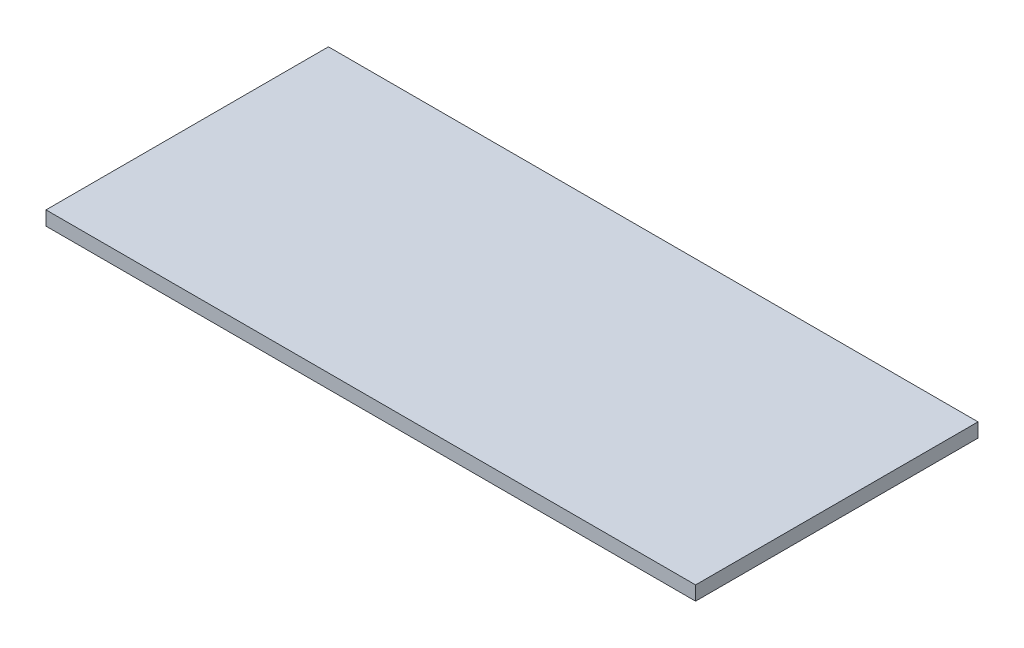
SolidWorks part; units mm, degrees
ref_plane "Front Plane" through (0, 0, 0) normal (0, 0, 1) x (1, 0, 0)
ref_plane "Top Plane" through (0, 0, 0) normal (0, 1, 0) x (1, 0, 0)
ref_plane "Right Plane" through (0, 0, 0) normal (1, 0, 0) x (0, 0, -1)
sketch "Sketch1" plane through (0, 0, 0) normal (0, 1, 0) x (1, 0, 0)
  line L0 (292.1, -254) -> (292.1, 0) construction
  line L1 (-292.1, -254) -> (292.1, -254)
  line L2 (-292.1, -254) -> (-292.1, 0)
  line L3 (-292.1, 0) -> (292.1, 0)
  line L4 (292.1, -254) -> (292.1, 0)
  line L5 (-292.1, -254) -> (292.1, 0) construction
  line L6 (-292.1, 0) -> (292.1, -254) construction
  line L7 (292.1, -254) -> (304.8, -254) construction
  point P0 (0, -127)
extrude "Boss-Extrude1" add sketch "Sketch1" along normal blind 12.7
